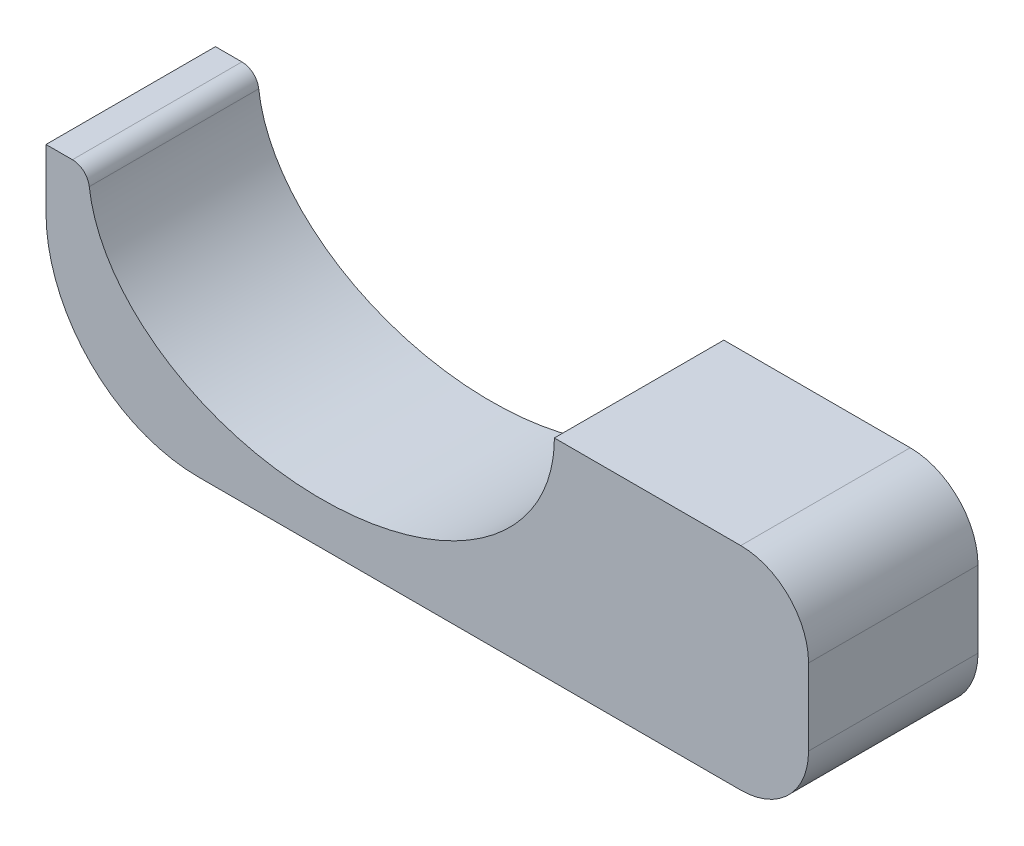
SolidWorks part; units mm, degrees
ref_plane "Front Plane" through (0, 0, 0) normal (0, 0, 1) x (1, 0, 0)
ref_plane "Top Plane" through (0, 0, 0) normal (0, 1, 0) x (1, 0, 0)
ref_plane "Right Plane" through (0, 0, 0) normal (1, 0, 0) x (0, 0, -1)
sketch "Sketch1" plane through (0, 0, 0) normal (0, 1, 0) x (1, 0, 0)
  line L1 (-57.15, 12.7) -> (57.15, 12.7)
  line L2 (-57.15, 12.7) -> (-57.15, -12.7)
  line L3 (-57.15, -12.7) -> (57.15, -12.7)
  line L4 (57.15, 12.7) -> (57.15, -12.7)
  line L5 (-57.15, 12.7) -> (57.15, -12.7) construction
  line L6 (-57.15, -12.7) -> (57.15, 12.7) construction
  point P1 (0, 0)
  dimension "D1" = 114.3
  dimension "D2" = 25.4
extrude "Boss-Extrude1" add sketch "Sketch1" along normal blind 31.75
sketch "Sketch2" plane through (0, 0, 12.7) normal (0, 0, 1) x (1, 0, 0)
  line L0 (-57.15, 31.75) -> (57.15, 31.75) construction
  ellipse E0 centre (-15.875, 31.75) end of major axis (-50.8, 31.75) minor radius 25.4
  dimension "D1" = 6.35
  dimension "D2" = 25.4
  dimension "D3" = 69.85
extrude "Cut-Extrude1" cut sketch "Sketch2" against normal through all
fillet "Fillet1" radius 2.54 1 edges at (-50.8, 31.75, 0)
fillet "Fillet2" radius 22.86 1 edges at (-57.15, 0, 0)
fillet "Fillet3" radius 10.16 2 edges at (57.15, 0, 0) (57.15, 31.75, 0)
sketch "Sketch3" plane through (0, 0, 12.7) normal (0, 0, 1) x (1, 0, 0)
  line L0 (23.1259, 27.8855) -> (21.1958, -1.4522)
  line L1 (32.6015, 27.9405) -> (33.9156, 10.7597)
  line L2 (33.9156, 10.7597) -> (33.9156, -7.0263)
  line L3 (33.9156, -7.0263) -> (32.6656, -11.4263)
  line L4 (32.6656, -11.4263) -> (23.9656, -11.4263)
  line L5 (23.9656, -11.4263) -> (22.0145, -6.082)
  arc A0 (32.6015, 27.9405) -> (23.1259, 27.8855) centre (27.8656, 27.5737) ccw
  arc A1 (21.1958, -1.4522) -> (22.0145, -6.082) centre (32.3651, -1.8643) ccw
